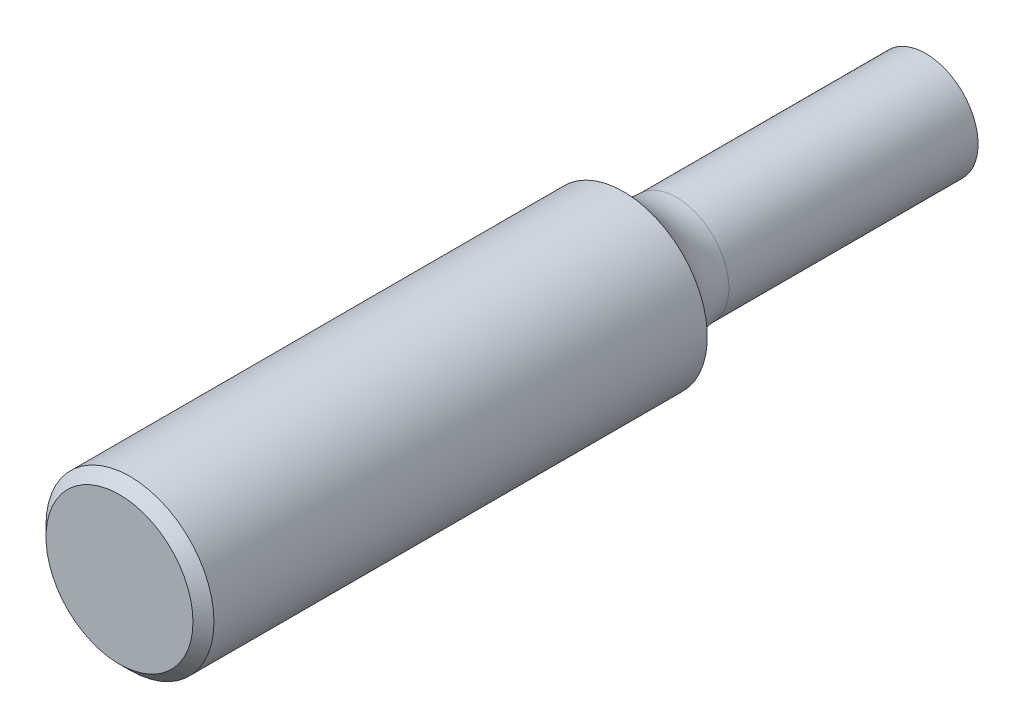
SolidWorks part; units mm, degrees
material "O1 Steel"
ref_plane "Alzado" through (0, 0, 0) normal (0, 0, 1) x (1, 0, 0)
ref_plane "Planta" through (0, 0, 0) normal (0, 1, 0) x (1, 0, 0)
ref_plane "Vista lateral" through (0, 0, 0) normal (1, 0, 0) x (0, 0, -1)
sketch "Croquis1" plane through (0, 0, 0) normal (1, 0, 0) x (0, 0, -1)
  line L0 (127, 0) -> (-127, 0) construction
  line L1 (-15.24, 0) -> (-15.24, 3.175)
  line L2 (-15.24, 3.175) -> (3.81, 3.175)
  line L4 (5.8182, 1.9812) -> (15.24, 1.9812)
  line L5 (15.24, 1.9812) -> (15.24, 0)
  line L6 (15.24, 0) -> (-15.24, 0)
  arc A0 (3.81, 3.175) -> (5.8182, 1.9812) centre (5.8182, 4.2672) ccw
  dimension "D6" = 2.286
  dimension "D1" = 254
  dimension "D2" = 6.35
  dimension "D3" = 30.48
  dimension "D4" = 19.05
  dimension "D5" = 3.9624
revolve "Revolución1" add sketch "Croquis1" angle 360 about L0
sketch "Croquis4" plane through (0, 0, 0) normal (1, 0, 0) x (0, 0, -1)
  line L0 (15.24, 0) -> (-15.24, 0) construction
  line L1 (15.24, -1.9812) -> (15.24, 1.9812) construction
  line L2 (-15.24, 3.175) -> (-15.24, -3.175) construction
  line L4 (14.732, 0) -> (15.24, 0)
  line L5 (15.24, 0) -> (15.24, 1.7227)
  arc A1 (14.732, 0) -> (15.24, 1.7227) centre (17.907, 0) cw
  dimension "D1" = 3.175
  dimension "D2" = 0.508
revolve "Cortar-Revolución1" cut sketch "Croquis4" angle 360 about L0
chamfer "Chaflán1" distance 0.3969 angle 45 1 edges at (-3.175, 0, 15.24)
